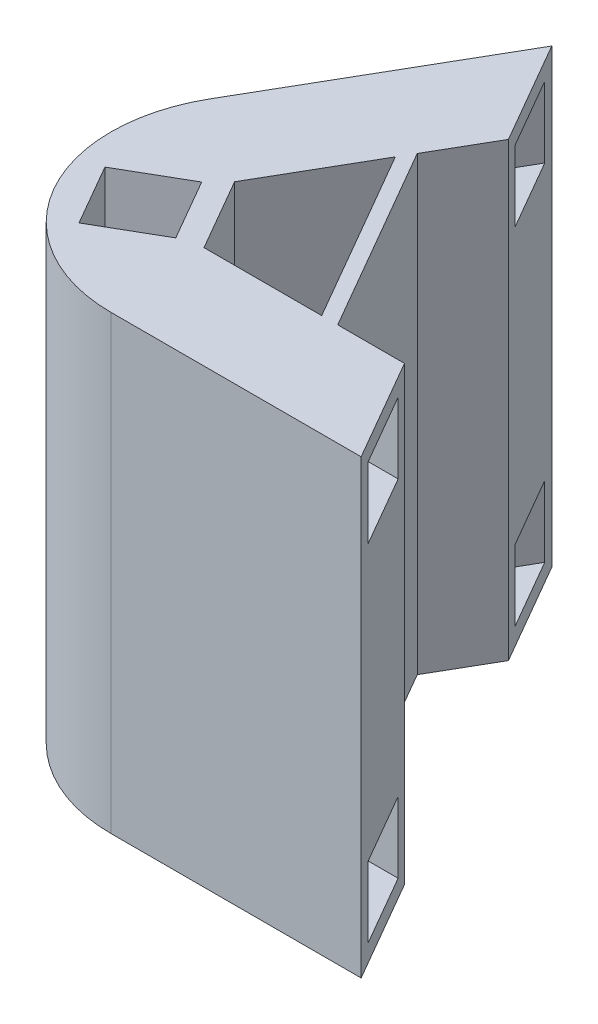
SolidWorks part; units mm, degrees
other "Markup1"
sketch "Sketch26" plane through (25.6218, 0, -129.9038) normal (-0.1134, -0.9932, -0.0259) x (0.9576, -0.1162, 0.2636)
ref_plane "Front Plane" through (0, 0, 0) normal (0, 0, 1) x (1, 0, 0)
ref_plane "Top Plane" through (0, 0, 0) normal (0, 1, 0) x (1, 0, 0)
ref_plane "Right Plane" through (0, 0, 0) normal (1, 0, 0) x (0, 0, -1)
sketch "Sketch1" plane through (0, 0, 0) normal (0, 1, 0) x (1, 0, 0)
  line L0 (0, 0) -> (150, 0)
  line L1 (0, 0) -> (75, 129.9038)
  line L2 (75, 129.9038) -> (150, 0)
  dimension "D1" = 60
  dimension "D2" = 150
  dimension "D3" = 60
extrude "Boss-Extrude1" add sketch "Sketch1" along normal blind 130
ref_plane "Plane1" through (0, 5, 0) normal (0, -1, 0) x (-1, 0, 0)
sketch "Sketch2" plane through (0, 5, 0) normal (0, 1, 0) x (1, 0, 0)
  line L0 (0, 0) -> (150, 0) construction
  line L1 (74, 5) -> (174, 5) construction
  line L2 (74, 5) -> (74, 25) construction
  line L3 (74, 25) -> (174, 25) construction
  line L4 (174, 5) -> (174, 25) construction
  line L5 (41.3301, 61.5859) -> (91.3301, 148.1884) construction
  line L6 (91.3301, 148.1884) -> (108.6506, 138.1884) construction
  line L7 (108.6506, 138.1884) -> (58.6506, 51.5859) construction
  line L8 (58.6506, 51.5859) -> (41.3301, 61.5859) construction
  line L9 (75, 129.9038) -> (0, 0) construction
  line L10 (108.9238, 138.2616) -> (58.7238, 51.3127)
  line L11 (58.7238, 51.3127) -> (41.0569, 61.5127)
  line L12 (41.0569, 61.5127) -> (91.2569, 148.4616)
  line L13 (91.2569, 148.4616) -> (108.9238, 138.2616)
  line L14 (73.8, 25.2) -> (174.2, 25.2)
  line L15 (174.2, 4.8) -> (174.2, 25.2)
  line L16 (73.8, 4.8) -> (174.2, 4.8)
  line L17 (73.8, 4.8) -> (73.8, 25.2)
  dimension "D1" = 20
  dimension "D2" = 5
  dimension "D3" = 74
  dimension "D4" = 20
  dimension "D5" = 74
  dimension "D6" = 5
  dimension "D7" = 100
  dimension "D8" = 100
  dimension "D9" = 0.2
  dimension "D10" = 0.2
extrude "Cut-Extrude2" cut sketch "Sketch2" along normal blind 20.4
ref_plane "Plane2" through (0, 65, 0) normal (0, 1, 0) x (1, 0, 0)
mirror "Mirror1" about plane through (0, 65, 0) normal (0, 1, 0) of "Cut-Extrude2"
sketch "Sketch4" plane through (0, 0, 0) normal (0, 1, 0) x (1, 0, 0)
  line L4 (150, 0) -> (75, 129.9038) construction
  line L5 (41.1219, 35.2887) -> (0, 0) construction
  line L6 (0, 0) -> (52.9457, 91.7047) construction
  line L7 (68.4424, 27.9682) -> (51.1219, 17.9682) construction
  line L8 (68.4424, 27.9682) -> (58.4424, 45.2887) construction
  line L9 (58.4424, 45.2887) -> (41.1219, 35.2887) construction
  line L10 (51.1219, 17.9682) -> (41.1219, 35.2887) construction
  line L11 (68.4424, 27.9682) -> (41.1219, 35.2887) construction
  line L12 (58.4424, 45.2887) -> (51.1219, 17.9682) construction
  line L13 (58.5156, 45.5619) -> (40.8487, 35.3619)
  line L14 (75, 129.9038) -> (0, 0) construction
  line L15 (0, 0) -> (130.8784, 0) construction
  line L16 (0, 0) -> (150, 0) construction
  line L17 (51.0487, 17.695) -> (40.8487, 35.3619)
  line L18 (68.7156, 27.895) -> (51.0487, 17.695)
  line L19 (68.7156, 27.895) -> (58.5156, 45.5619)
  line L20 (51.1219, 17.9682) -> (0, 0) construction
  point P0 (54.7821, 31.6285)
  dimension "D1" = 20
  dimension "D2" = 20
  dimension "D3" = 21.269
  dimension "D4" = 0.2
  dimension "D5" = 54.1877
extrude "Cut-Extrude3" cut sketch "Sketch4" along normal through all
fillet "Fillet1" radius 45 1 edges at (0, 65, 0)
sketch "Sketch27" plane through (0, 0, 0) normal (0, -1, 0) x (1, 0, 0)
  line L0 (132.9508, -29.5301) -> (75.2157, -29.5301)
  line L1 (150, 0) -> (75, -129.9038) construction
  line L2 (75.2157, -29.5301) -> (63.1817, -50.3737)
  line L3 (63.1817, -50.3737) -> (92.0492, -100.3737)
  line L4 (135.4508, -25.2) -> (73.8, -25.2) construction
  line L5 (58.7238, -51.3127) -> (89.5492, -104.7038) construction
  dimension "D1" = 5
  dimension "D2" = 5
  dimension "D3" = 50
extrude "Cut-Extrude4" cut sketch "Sketch27" against normal through all and the other way through all
sketch "Sketch28" plane through (0, 0, 0) normal (0, -1, 0) x (1, 0, 0)
  line L0 (109.1062, -29.5301) -> (80.1269, -79.7237)
  line L1 (75.2157, -29.5301) -> (132.9508, -29.5301) construction
  line L2 (92.0492, -100.3737) -> (63.1817, -50.3737) construction
  line L3 (80.1269, -79.7237) -> (82.4363, -83.7237)
  line L4 (82.4363, -83.7237) -> (113.725, -29.5301)
  line L5 (113.725, -29.5301) -> (109.1062, -29.5301)
  line L6 (63.1817, -50.3737) -> (75.2157, -29.5301) construction
  dimension "D1" = 4
  dimension "D2" = 33.35
extrude "Boss-Extrude2" add sketch "Sketch28" against normal up to surface (130 mm away) up to face at (54.7821, 130, -31.6285)
